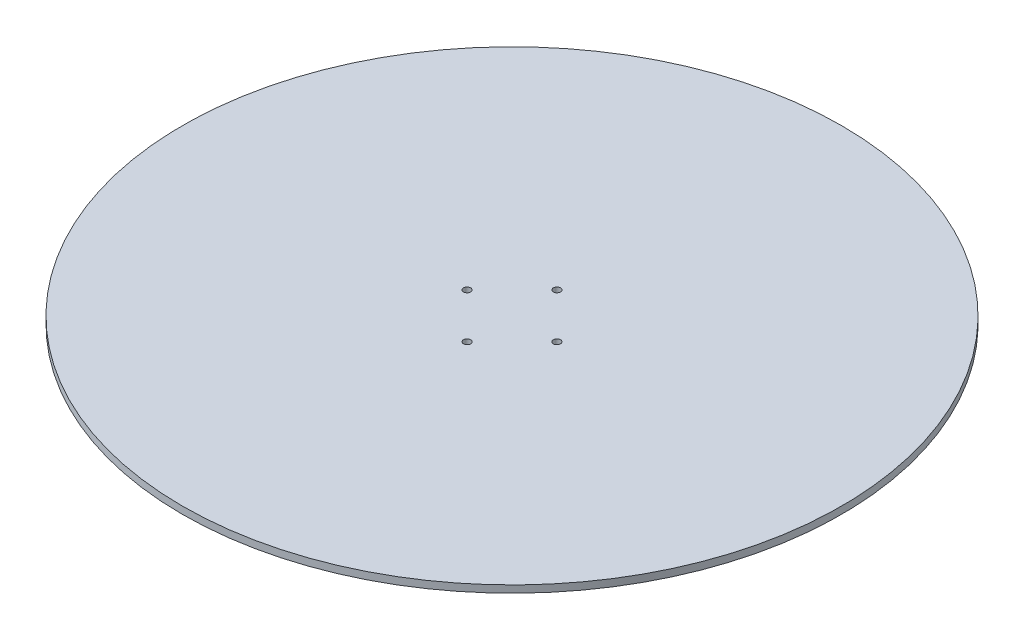
SolidWorks part; units mm, degrees
material "Acrílico (médio-alto impacto)"
ref_plane "Plano frontal" through (0, 0, 0) normal (0, 0, 1) x (1, 0, 0)
ref_plane "Plano superior" through (0, 0, 0) normal (0, 1, 0) x (1, 0, 0)
ref_plane "Plano direito" through (0, 0, 0) normal (1, 0, 0) x (0, 0, -1)
sketch "Esboço1" plane through (0, 0, 0) normal (0, 1, 0) x (1, 0, 0)
  circle A0 centre (0, 0) radius 275
  dimension "D1" = 550
extrude "Ressalto-extrusão1" add sketch "Esboço1" along normal blind 6
hole_wizard "Furo de diâmetro Ø6.0 (6)1" positions "Esboço2" profile "Esboço3" hole size "Ø6.0" standard "ISO" end condition through all
sketch "Esboço2" plane through (0, 6, 0) normal (0, 1, 0) x (1, 0, 0)
  circle A0 centre (0, 0) radius 37.5 construction
  point P5 (0, 37.5)
  point P7 (37.5, 0)
  point P9 (0, -37.5)
  point P11 (-37.5, 0)
  dimension "D1" = 75
sketch "Esboço3" plane through (0, 6, -37.5) normal (1, 0, 0) x (0, 0, 1)
  line L0 (0, 0) -> (0, 6)
  line L1 (0, 6) -> (3, 6)
  line L2 (3, 6) -> (3, 0)
  line L5 (3, 0) -> (0, 0)
  line L11 (0, -6.35) -> (0, 107.95) construction
  dimension "Thru Hole Dia." = 6
  dimension "Thru Hole Depth" = 6
